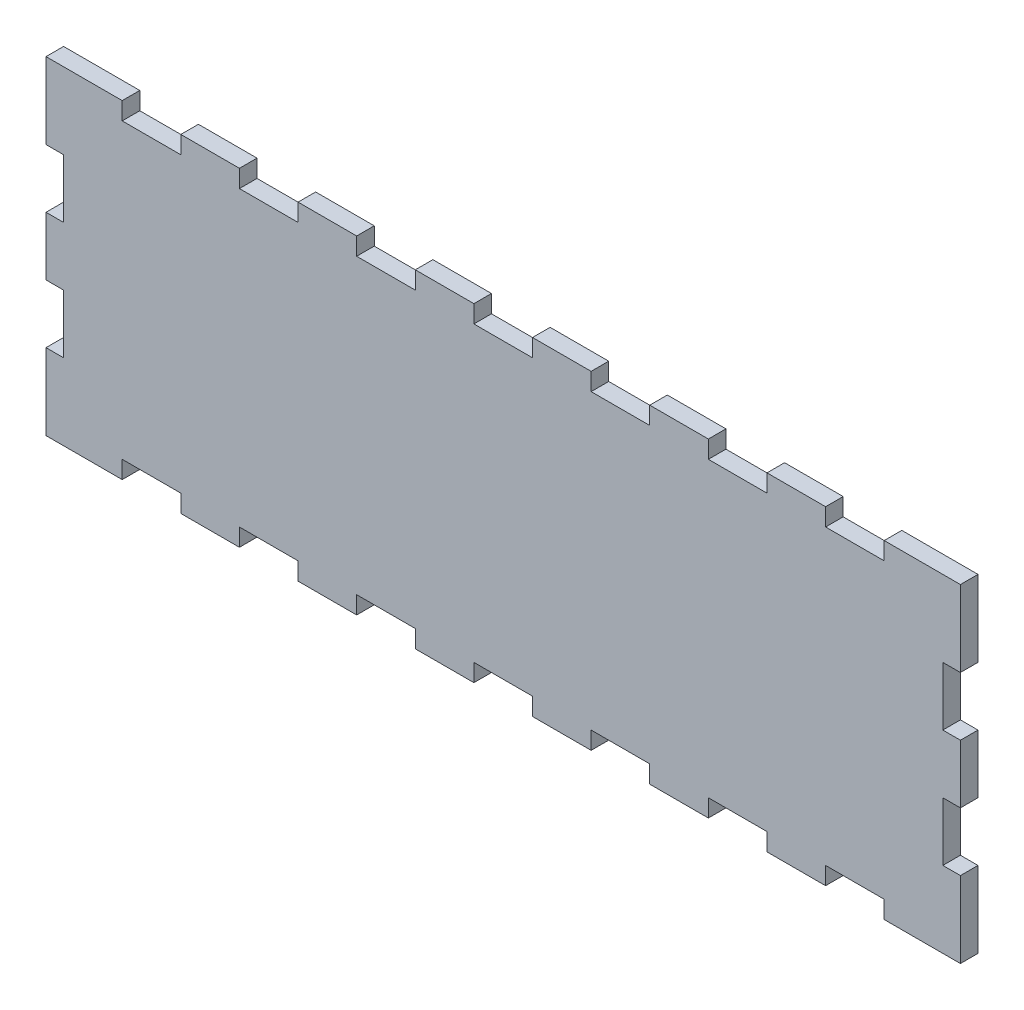
SolidWorks part; units mm, degrees
ref_plane "Front Plane" through (0, 0, 0) normal (0, 0, 1) x (1, 0, 0)
ref_plane "Top Plane" through (0, 0, 0) normal (0, 1, 0) x (1, 0, 0)
ref_plane "Right Plane" through (0, 0, 0) normal (1, 0, 0) x (0, 0, -1)
sketch "Sketch1" plane through (0, 0, 0) normal (0, 0, 1) x (1, 0, 0)
  line L0 (15, 28) -> (15, 25)
  line L1 (-76.5, 26.5) -> (76.5, 26.5) construction
  line L2 (-76.5, 26.5) -> (-76.5, -26.5) construction
  line L3 (-76.5, -26.5) -> (76.5, -26.5) construction
  line L4 (76.5, 26.5) -> (76.5, -26.5) construction
  line L5 (-76.5, 26.5) -> (76.5, -26.5) construction
  line L6 (-76.5, -26.5) -> (76.5, 26.5) construction
  line L7 (-5, 28) -> (5, 28) construction
  line L8 (-5, 28) -> (-5, 25)
  line L9 (-5, 25) -> (5, 25)
  line L10 (5, 28) -> (5, 25)
  line L11 (-5, 28) -> (5, 25) construction
  line L12 (-5, 25) -> (5, 28) construction
  line L13 (15, 25) -> (25, 25)
  line L14 (25, 28) -> (25, 25)
  line L15 (35, 28) -> (35, 25)
  line L16 (35, 25) -> (45, 25)
  line L17 (45, 28) -> (45, 25)
  line L18 (55, 28) -> (55, 25)
  line L19 (55, 25) -> (65, 25)
  line L20 (65, 28) -> (65, 25)
  line L21 (5, 28) -> (15, 28)
  line L22 (25, 28) -> (35, 28)
  line L23 (45, 28) -> (55, 28)
  line L24 (65, 28) -> (78, 28)
  line L25 (-25, 25) -> (-15, 25)
  line L26 (-25, 28) -> (-25, 25)
  line L27 (-15, 28) -> (-15, 25)
  line L28 (-45, 25) -> (-35, 25)
  line L29 (-45, 28) -> (-45, 25)
  line L30 (-35, 28) -> (-35, 25)
  line L31 (-65, 25) -> (-55, 25)
  line L32 (-65, 28) -> (-65, 25)
  line L33 (-55, 28) -> (-55, 25)
  line L34 (-55, 28) -> (-45, 28)
  line L35 (-35, 28) -> (-25, 28)
  line L36 (-15, 28) -> (-5, 28)
  line L37 (-65, 28) -> (-78, 28)
  line L38 (0, 0) -> (10.7491, 0) construction
  line L39 (0, 0) -> (0, 9.6256) construction
  line L40 (65, -28) -> (78, -28)
  line L41 (65, -28) -> (65, -25)
  line L42 (55, -25) -> (65, -25)
  line L43 (55, -28) -> (55, -25)
  line L44 (45, -28) -> (55, -28)
  line L45 (45, -28) -> (45, -25)
  line L46 (35, -25) -> (45, -25)
  line L47 (35, -28) -> (35, -25)
  line L48 (25, -28) -> (35, -28)
  line L49 (25, -28) -> (25, -25)
  line L50 (15, -25) -> (25, -25)
  line L51 (15, -28) -> (15, -25)
  line L52 (5, -28) -> (15, -28)
  line L53 (5, -28) -> (5, -25)
  line L54 (-5, -25) -> (5, -25)
  line L55 (-5, -28) -> (-5, -25)
  line L56 (-15, -28) -> (-5, -28)
  line L57 (-15, -28) -> (-15, -25)
  line L58 (-25, -25) -> (-15, -25)
  line L59 (-25, -28) -> (-25, -25)
  line L60 (-35, -28) -> (-25, -28)
  line L61 (-35, -28) -> (-35, -25)
  line L62 (-45, -25) -> (-35, -25)
  line L63 (-45, -28) -> (-45, -25)
  line L64 (-55, -28) -> (-45, -28)
  line L65 (-55, -28) -> (-55, -25)
  line L66 (-65, -25) -> (-55, -25)
  line L67 (-65, -28) -> (-65, -25)
  line L68 (-65, -28) -> (-78, -28)
  line L69 (78, 28) -> (78, 15)
  line L70 (78, -28) -> (78, -15)
  line L71 (75, -5) -> (78, -5)
  line L72 (75, -5) -> (75, -15)
  line L73 (75, -15) -> (78, -15)
  line L74 (78, -5) -> (78, -15) construction
  line L75 (75, -5) -> (78, -15) construction
  line L76 (75, -15) -> (78, -5) construction
  line L77 (75, 15) -> (75, 5)
  line L78 (75, 15) -> (78, 15)
  line L79 (75, 5) -> (78, 5)
  line L80 (78, -5) -> (78, 5)
  line L81 (-78, -28) -> (-78, -15)
  line L82 (-75, -15) -> (-78, -15)
  line L83 (-75, -5) -> (-75, -15)
  line L84 (-75, -5) -> (-78, -5)
  line L85 (-78, -5) -> (-78, 5)
  line L86 (-75, 5) -> (-78, 5)
  line L87 (-75, 15) -> (-75, 5)
  line L88 (-75, 15) -> (-78, 15)
  line L89 (-78, 28) -> (-78, 15)
  point P0 (0, 0)
  point P6 (0, 26.5)
  point P70 (76.5, -10)
  dimension "D1" = 153
  dimension "D2" = 53
  dimension "D3" = 10
  dimension "D4" = 3
  dimension "D7" = 10
  dimension "D9" = 10
  dimension "D10" = 13
  dimension "D11" = 10
  dimension "D12" = 13
  dimension "D13" = 13
  dimension "D5" = 4
  dimension "D8" = 4
  dimension "D14" = 2
extrude "Boss-Extrude1" add sketch "Sketch1" along normal blind 3
